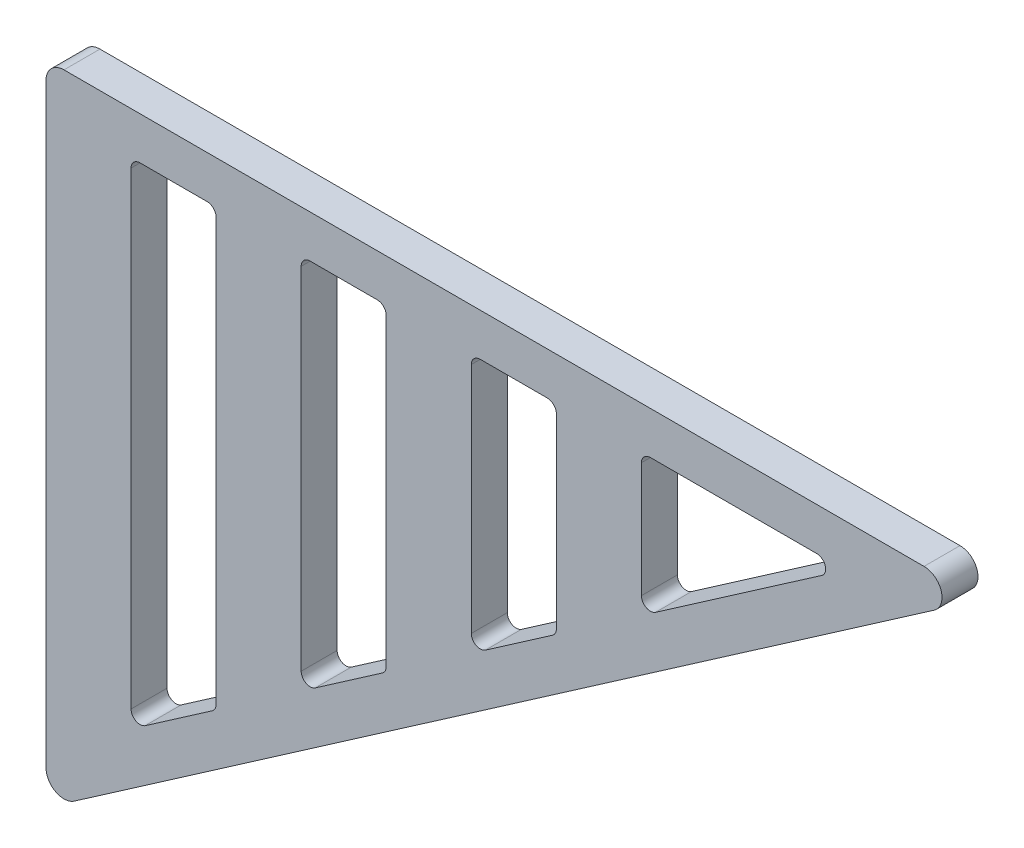
SolidWorks part; units mm, degrees
ref_plane "Front Plane" through (0, 0, 0) normal (0, 0, 1) x (1, 0, 0)
ref_plane "Top Plane" through (0, 0, 0) normal (0, 1, 0) x (1, 0, 0)
ref_plane "Right Plane" through (0, 0, 0) normal (1, 0, 0) x (0, 0, -1)
sketch "Sketch1" plane through (0, 0, 0) normal (0, 0, 1) x (1, 0, 0)
  line L0 (0, 48.4776) -> (0, 889)
  line L1 (25.4, 914.4) -> (1239.4879, 914.4)
  line L2 (1253.9458, 868.1163) -> (39.8579, 27.594)
  line L3 (120.0727, 180.386) -> (120.0727, 841.6636)
  line L4 (132.7727, 854.3636) -> (227.4455, 854.3636)
  line L5 (240.1455, 841.6636) -> (240.1455, 245.9286)
  line L6 (234.6744, 235.4868) -> (140.0017, 169.9441)
  line L7 (360.2182, 346.6405) -> (360.2182, 841.6636)
  line L8 (372.9182, 854.3636) -> (467.5909, 854.3636)
  line L9 (480.2909, 841.6636) -> (480.2909, 412.1832)
  line L10 (474.8199, 401.7413) -> (380.1471, 336.1987)
  line L11 (600.3636, 512.895) -> (600.3636, 841.6636)
  line L12 (613.0636, 854.3636) -> (707.7364, 854.3636)
  line L13 (720.4364, 841.6636) -> (720.4364, 578.4377)
  line L14 (714.9653, 567.9959) -> (620.2926, 502.4532)
  line L15 (840.5091, 679.1496) -> (840.5091, 841.6636)
  line L22 (853.2091, 854.3636) -> (1087.9516, 854.3636)
  line L23 (1095.1806, 831.2218) -> (860.4381, 668.7078)
  arc A0 (1253.9458, 868.1163) -> (1239.4879, 914.4) centre (1239.4879, 889) ccw
  arc A1 (39.8579, 27.594) -> (0, 48.4776) centre (25.4, 48.4776) cw
  arc A2 (0, 889) -> (25.4, 914.4) centre (25.4, 889) cw
  arc A3 (1087.9516, 854.3636) -> (1095.1806, 831.2218) centre (1087.9516, 841.6636) cw
  arc A4 (840.5091, 841.6636) -> (853.2091, 854.3636) centre (853.2091, 841.6636) cw
  arc A5 (840.5091, 679.1496) -> (860.4381, 668.7078) centre (853.2091, 679.1496) ccw
  arc A6 (720.4364, 578.4377) -> (714.9653, 567.9959) centre (707.7364, 578.4377) cw
  arc A7 (600.3636, 512.895) -> (620.2926, 502.4532) centre (613.0636, 512.895) ccw
  arc A8 (707.7364, 854.3636) -> (720.4364, 841.6636) centre (707.7364, 841.6636) cw
  arc A9 (600.3636, 841.6636) -> (613.0636, 854.3636) centre (613.0636, 841.6636) cw
  arc A10 (467.5909, 854.3636) -> (480.2909, 841.6636) centre (467.5909, 841.6636) cw
  arc A11 (360.2182, 841.6636) -> (372.9182, 854.3636) centre (372.9182, 841.6636) cw
  arc A12 (480.2909, 412.1832) -> (474.8199, 401.7413) centre (467.5909, 412.1832) cw
  arc A13 (360.2182, 346.6405) -> (380.1471, 336.1987) centre (372.9182, 346.6405) ccw
  arc A14 (240.1455, 245.9286) -> (234.6744, 235.4868) centre (227.4455, 245.9286) cw
  arc A15 (120.0727, 180.386) -> (140.0017, 169.9441) centre (132.7727, 180.386) ccw
  arc A16 (227.4455, 854.3636) -> (240.1455, 841.6636) centre (227.4455, 841.6636) cw
  arc A17 (120.0727, 841.6636) -> (132.7727, 854.3636) centre (132.7727, 841.6636) cw
  point P6 (1320.8, 914.4)
  point P9 (0, 0)
  point P12 (0, 914.4)
  point P40 (720.4364, 854.3636)
  point P43 (600.3636, 854.3636)
  point P58 (240.1455, 854.3636)
  point P61 (120.0727, 854.3636)
  dimension "D3" = 25.4
  dimension "D4" = 25.4
  dimension "D5" = 25.4
  dimension "D21" = 12.7
  dimension "D1" = 914.4
  dimension "D2" = 1320.8
  dimension "D6" = 120.0727
  dimension "D7" = 120.0727
  dimension "D8" = 120.0727
  dimension "D9" = 120.0727
  dimension "D10" = 120.0727
  dimension "D11" = 120.0727
  dimension "D12" = 120.0727
  dimension "D13" = 60.0364
  dimension "D14" = 60.0364
  dimension "D15" = 60.0364
  dimension "D16" = 60.0364
  dimension "D17" = 60.0364
  dimension "D18" = 60.0364
  dimension "D19" = 60.0364
  dimension "D20" = 60.0364
extrude "Boss-Extrude2" add sketch "Sketch1" along normal blind 50.8
